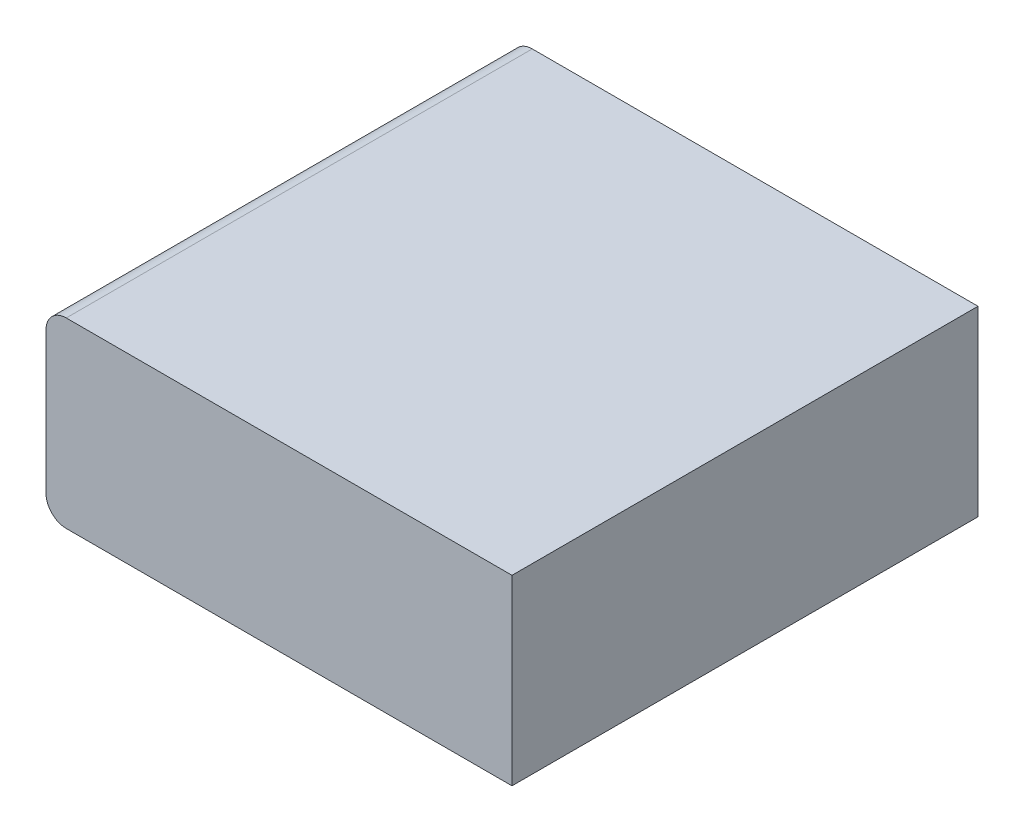
SolidWorks part; units mm, degrees
ref_plane "Front Plane" through (0, 0, 0) normal (0, 0, 1) x (1, 0, 0)
ref_plane "Top Plane" through (0, 0, 0) normal (0, 1, 0) x (1, 0, 0)
ref_plane "Right Plane" through (0, 0, 0) normal (1, 0, 0) x (0, 0, -1)
sketch "Sketch1" plane through (0, 0, 0) normal (0, 1, 0) x (1, 0, 0)
  line L1 (0, 0) -> (460, 0)
  line L2 (0, 0) -> (0, 460)
  line L3 (0, 460) -> (460, 460)
  line L4 (460, 0) -> (460, 460)
  dimension "D1" = 460
  dimension "D2" = 460
extrude "Boss-Extrude1" add sketch "Sketch1" along normal blind 180
fillet "Fillet1" radius 20 2 edges at (0, 0, -230) (0, 180, -230)
